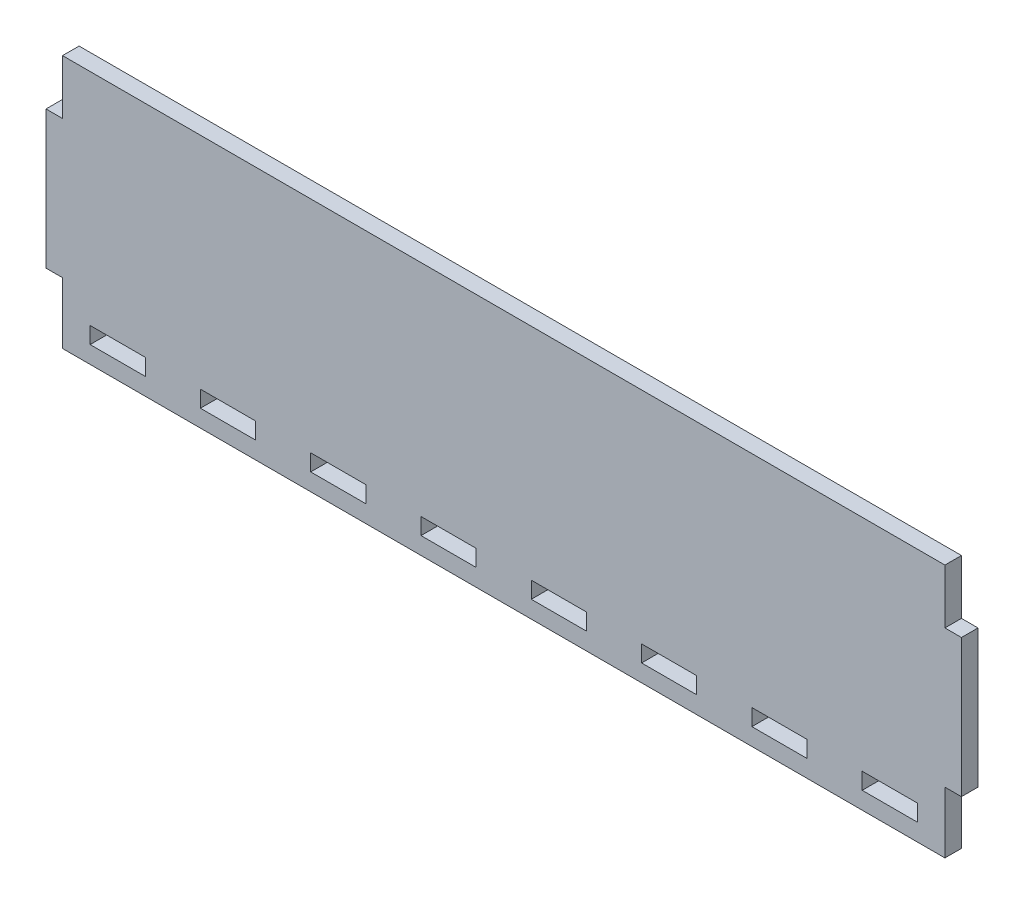
SolidWorks part; units mm, degrees
ref_plane "Front Plane" through (0, 0, 0) normal (0, 0, 1) x (1, 0, 0)
ref_plane "Top Plane" through (0, 0, 0) normal (0, 1, 0) x (1, 0, 0)
ref_plane "Right Plane" through (0, 0, 0) normal (1, 0, 0) x (0, 0, -1)
sketch "Sketch1" plane through (0, 0, 0) normal (0, 0, 1) x (1, 0, 0)
  line L0 (-6.3615, -18.573) -> (-6.3615, -21.573)
  line L1 (-31.3615, 21.3052) -> (128.6385, 21.3052)
  line L2 (-31.3615, 21.3052) -> (-31.3615, 11.427)
  line L3 (-31.3615, -24.6948) -> (128.6385, -24.6948)
  line L4 (128.6385, 21.3052) -> (128.6385, 11.427)
  line L5 (-26.3615, -18.573) -> (-16.3615, -18.573)
  line L6 (-26.3615, -18.573) -> (-26.3615, -21.573)
  line L7 (-26.3615, -21.573) -> (-16.3615, -21.573)
  line L8 (-16.3615, -18.573) -> (-16.3615, -21.573)
  line L9 (-6.3615, -18.573) -> (3.6385, -18.573)
  line L10 (3.6385, -18.573) -> (3.6385, -21.573)
  line L11 (-6.3615, -21.573) -> (3.6385, -21.573)
  line L12 (13.6385, -18.573) -> (13.6385, -21.573)
  line L13 (13.6385, -18.573) -> (23.6385, -18.573)
  line L14 (23.6385, -18.573) -> (23.6385, -21.573)
  line L15 (13.6385, -21.573) -> (23.6385, -21.573)
  line L16 (33.6385, -18.573) -> (33.6385, -21.573)
  line L17 (33.6385, -18.573) -> (43.6385, -18.573)
  line L18 (43.6385, -18.573) -> (43.6385, -21.573)
  line L19 (33.6385, -21.573) -> (43.6385, -21.573)
  line L20 (53.6385, -18.573) -> (53.6385, -21.573)
  line L21 (53.6385, -18.573) -> (63.6385, -18.573)
  line L22 (63.6385, -18.573) -> (63.6385, -21.573)
  line L23 (53.6385, -21.573) -> (63.6385, -21.573)
  line L24 (73.6385, -18.573) -> (73.6385, -21.573)
  line L25 (73.6385, -18.573) -> (83.6385, -18.573)
  line L26 (83.6385, -18.573) -> (83.6385, -21.573)
  line L27 (73.6385, -21.573) -> (83.6385, -21.573)
  line L28 (93.6385, -18.573) -> (93.6385, -21.573)
  line L29 (93.6385, -18.573) -> (103.6385, -18.573)
  line L30 (103.6385, -18.573) -> (103.6385, -21.573)
  line L31 (93.6385, -21.573) -> (103.6385, -21.573)
  line L32 (113.6385, -18.573) -> (113.6385, -21.573)
  line L33 (113.6385, -18.573) -> (123.6385, -18.573)
  line L34 (123.6385, -18.573) -> (123.6385, -21.573)
  line L35 (113.6385, -21.573) -> (123.6385, -21.573)
  line L36 (-31.3615, -13.573) -> (-31.3615, -24.6948)
  line L37 (-31.3615, 11.427) -> (-34.3615, 11.427)
  line L39 (-31.3615, -13.573) -> (-34.3615, -13.573)
  line L40 (-34.3615, 11.427) -> (-34.3615, -13.573)
  line L41 (128.6385, 11.427) -> (131.6385, 11.427)
  line L43 (128.6385, -13.573) -> (131.6385, -13.573)
  line L44 (131.6385, 11.427) -> (131.6385, -13.573)
  line L45 (128.6385, -13.573) -> (128.6385, -24.6948)
  point P44 (0, 0)
  dimension "D1" = 46
  dimension "D2" = 160
  dimension "D3" = 5
  dimension "3" = 3.1219
  dimension "D4" = 3
  dimension "D5" = 8
  dimension "10" = 10
  dimension "D6" = 5
  dimension "D7" = 25
  dimension "D8" = 3
  dimension "D9" = 5
  dimension "D10" = 25
  dimension "D11" = 3
  dimension "D12" = 5
extrude "Boss-Extrude1" add sketch "Sketch1" along normal blind 3 contours L20 L23 L22 L21 | L16 L19 L18 L17 | L0 L11 L10 L9 | L1 L4 L41 L44 L43 L45 L3 L36 L39 L40 L37 L2 | L33 L34 L35 L32 | L31 L30 L29 L28 | L27 L26 L25 L24 | L15 L14 L13 L12 | L5 L8 L7 L6
